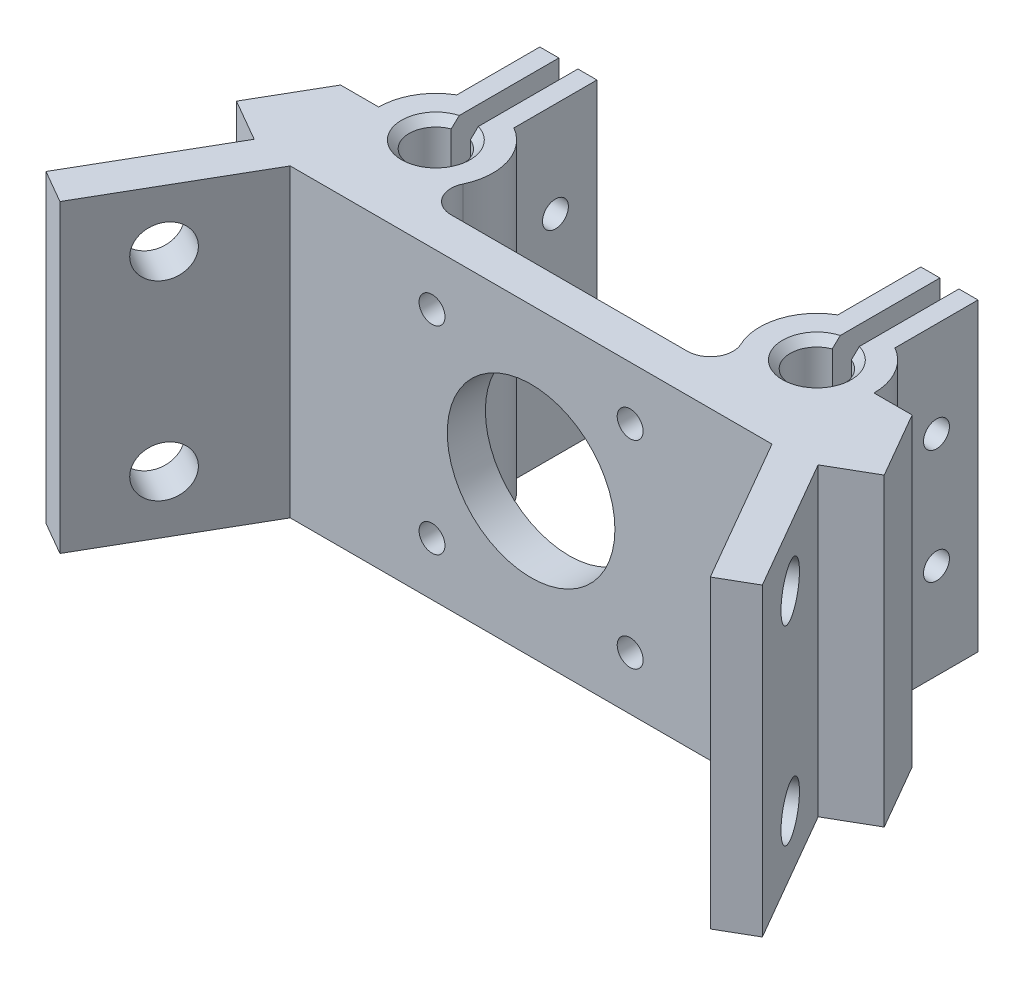
SolidWorks part; units mm, degrees
ref_plane "Front Plane" through (0, 0, 0) normal (0, 0, 1) x (1, 0, 0)
ref_plane "Top Plane" through (0, 0, 0) normal (0, 1, 0) x (1, 0, 0)
ref_plane "Right Plane" through (0, 0, 0) normal (1, 0, 0) x (0, 0, -1)
sketch "Sketch1" plane through (0, 0, 0) normal (0, 1, 0) x (1, 0, 0)
  line L0 (0, 116.7614) -> (0, -100.8523) construction
  line L1 (23.75, 120.7692) -> (23.75, 134.8951)
  line L2 (28.75, 134.8951) -> (28.75, 123.9952)
  line L3 (25, -2.1466) -> (25, 14.9187) construction
  line L4 (23.75, 134.8951) -> (21.25, 134.8951)
  line L5 (21.25, 134.8951) -> (21.25, 123.9952)
  line L6 (26.25, 134.8951) -> (28.75, 134.8951)
  line L7 (26.25, 120.7692) -> (26.25, 134.8951)
  line L8 (-25, -0.2491) -> (-25, 16.8161) construction
  line L9 (-26.25, 120.7692) -> (-26.25, 134.8951)
  line L10 (-26.25, 134.8951) -> (-28.75, 134.8951)
  line L11 (-21.25, 134.8951) -> (-21.25, 123.9952)
  line L12 (-23.75, 134.8951) -> (-21.25, 134.8951)
  line L13 (-28.75, 134.8951) -> (-28.75, 123.9952)
  line L14 (-23.75, 120.7692) -> (-23.75, 134.8951)
  line L15 (-15.5132, 110) -> (15.5132, 110)
  line L16 (-31.611, 105) -> (31.611, 105)
  line L17 (-32.5, 117.5) -> (-37.5, 117.5)
  line L18 (0, 110) -> (-95.2628, -55) construction
  line L19 (-95.2628, -55) -> (95.2628, -55) construction
  line L20 (95.2628, -55) -> (0, 110) construction
  line L21 (-37.5, 117.5) -> (-42.5, 108.8397)
  line L22 (-47.0007, 88.3442) -> (-42.6706, 85.8442)
  line L23 (-42.6706, 85.8442) -> (-31.611, 105)
  line L24 (42.6706, 85.8442) -> (31.611, 105)
  line L25 (47.0007, 88.3442) -> (42.6706, 85.8442)
  line L26 (47.0007, 88.3442) -> (37.0007, 105.6647)
  line L27 (32.5, 117.5) -> (37.5, 117.5)
  line L28 (-47.0007, 88.3442) -> (-37.0007, 105.6647)
  line L29 (-37.0007, 105.6647) -> (-42.5, 108.8397)
  line L30 (37.0007, 105.6647) -> (42.5, 108.8397)
  line L31 (37.5, 117.5) -> (42.5, 108.8397)
  arc A0 (21.25, 123.9952) -> (18.2237, 114.2857) centre (25, 117.5) ccw
  arc A1 (23.75, 120.7692) -> (26.25, 120.7692) centre (25, 117.5) ccw
  arc A2 (-23.75, 120.7692) -> (-26.25, 120.7692) centre (-25, 117.5) cw
  arc A3 (-21.25, 123.9952) -> (-18.2237, 114.2857) centre (-25, 117.5) cw
  circle A4 centre (0, 0) radius 110 construction
  circle A5 centre (0, 0) radius 55 construction
  arc A6 (15.5132, 110) -> (18.2237, 114.2857) centre (15.5132, 113) ccw
  arc A7 (-18.2237, 114.2857) -> (-15.5132, 110) centre (-15.5132, 113) ccw
  arc A8 (-28.75, 123.9952) -> (-32.5, 117.5) centre (-25, 117.5) ccw
  arc A9 (28.75, 123.9952) -> (32.5, 117.5) centre (25, 117.5) cw
  point P12 (23.75, 124.8951)
  point P13 (26.25, 124.8951)
  point P27 (-26.25, 124.8951)
  point P28 (-23.75, 124.8951)
  point P67 (0, 0)
  dimension "D2" = 7
  dimension "D3" = 4
  dimension "D5" = 2.5
  dimension "D10" = 120
  dimension "D11" = 10
  dimension "D7" = 220
  dimension "D13" = 3
  dimension "D14" = 7.5
  dimension "D1" = 50
  dimension "D4" = 10
  dimension "D6" = 2.5
  dimension "D8" = 5
  dimension "D9" = 5
  dimension "D12" = 5
  dimension "D15" = 20
  dimension "D16" = 6.35
extrude "Boss-Extrude1" add sketch "Sketch1" along normal blind 40
sketch "Sketch2" plane through (0, 0, 0) normal (1, 0, 0) x (0, 0, -1)
  line L0 (129.4451, 40) -> (129.4451, 0) construction
  line L3 (134.8951, 20) -> (113.9952, 20) construction
  line L4 (134.8951, 40) -> (134.8951, 0) construction
  line L6 (134.8951, 40) -> (123.9952, 40) construction
  line L7 (134.8951, 0) -> (123.9952, 0) construction
  circle A0 centre (129.4451, 27.5) radius 1.7
  circle A1 centre (129.4451, 12.5) radius 1.7
  dimension "D1" = 3.4
  dimension "D2" = 15
extrude "Cut-Extrude1" cut sketch "Sketch2" against normal mid plane 57.5
sketch "Sketch4" plane through (0, 0, -105) normal (0, 0, 1) x (1, 0, 0)
  line L1 (-13, 7) -> (13, 7) construction
  line L2 (-13, 7) -> (-13, 33) construction
  line L3 (-13, 33) -> (13, 33) construction
  line L4 (13, 7) -> (13, 33) construction
  line L5 (-13, 7) -> (13, 33) construction
  line L6 (-13, 33) -> (13, 7) construction
  line L7 (17.75, 2.25) -> (-17.75, 2.25)
  line L8 (17.75, 2.25) -> (17.75, 37.75)
  line L9 (17.75, 37.75) -> (-17.75, 37.75)
  line L10 (-17.75, 2.25) -> (-17.75, 37.75)
  line L11 (17.75, 2.25) -> (-17.75, 37.75) construction
  line L12 (17.75, 37.75) -> (-17.75, 2.25) construction
  circle A0 centre (-13, 33) radius 1.7
  circle A1 centre (13, 33) radius 1.7
  circle A2 centre (13, 7) radius 1.7
  circle A3 centre (-13, 7) radius 1.7
  circle A4 centre (0, 20) radius 11
  circle A5 centre (-13, 33) radius 2.9337 construction
  point P0 (0, 20)
  point P16 (0, 20)
  dimension "D2" = 3.4
  dimension "D5" = 22
  dimension "D7" = 5.8674
  dimension "D1" = 26
  dimension "D4" = 20
  dimension "D6" = 35.5
  dimension "D3" = 4
extrude "Cut-Extrude2" cut sketch "Sketch4" against normal blind 20 contours A0 | A4 | A1 | A2 | A3
chamfer "Chamfer1" distance 1 angle 45 2 edges at (25, 40, -114) (-25, 40, -114)
sketch "Sketch5" plane through (-73.5047, 0, -42.438) normal (-0.866, 0, -0.5) x (-0.5, 0, 0.866)
  line L0 (-53.008, 20) -> (-73.008, 20) construction
  line L1 (-53.008, 40) -> (-53.008, 0) construction
  line L2 (-73.008, 40) -> (-73.008, 0) construction
  line L3 (-63.008, 20) -> (-63.008, 32.5) construction
  line L4 (-63.008, 20) -> (-63.008, 7.5) construction
  circle A0 centre (-63.008, 32.5) radius 3.3
  circle A1 centre (-63.008, 7.5) radius 3.3
  dimension "D1" = 10
  dimension "D2" = 6.6
  dimension "D3" = 25
extrude "Cut-Extrude3" cut sketch "Sketch5" against normal up to next
mirror "Mirror1" about plane through (0, 0, 0) normal (1, 0, 0) of "Cut-Extrude3"
equation "\"RodSpacing\"= 50"
equation "\"D1@Sketch1\"=\"RodSpacing\""
equation "\"Clamp_Gap\"=2.5"
equation "\"D5@Sketch1\"=\"Clamp_Gap\""
equation "\"D6@Sketch1\"=\"Clamp_Gap\""
equation "\"D1@Cut-Extrude1\"=\"RodSpacing\"+(3*\"Clamp_Gap\")"
